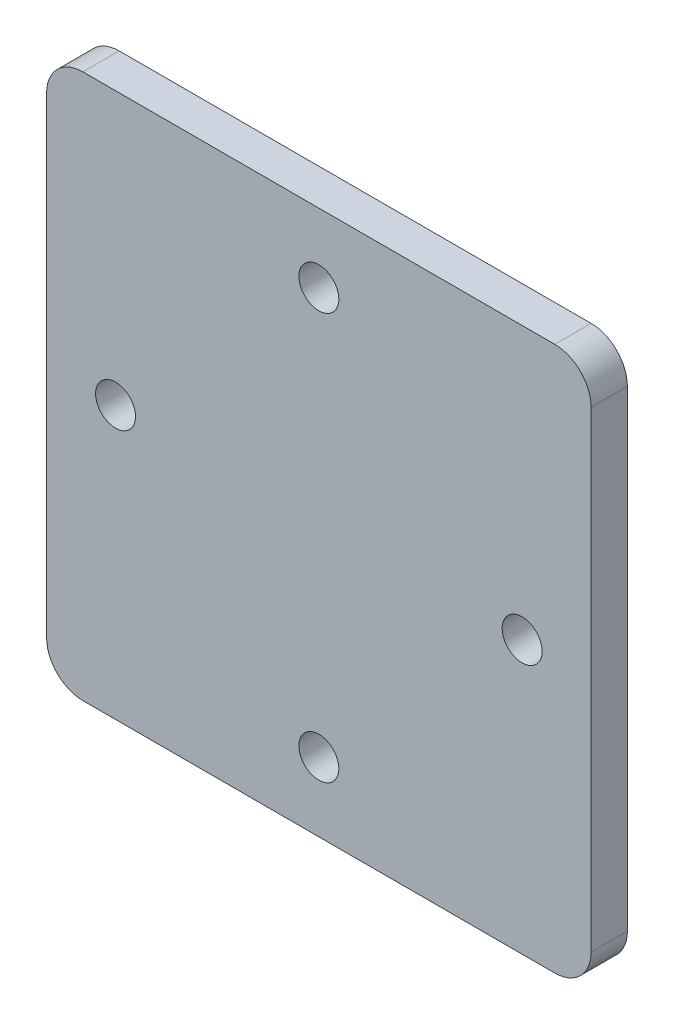
SolidWorks part; units mm, degrees
ref_plane "Frontale" through (0, 0, 0) normal (0, 0, 1) x (1, 0, 0)
ref_plane "Superiore" through (0, 0, 0) normal (0, 1, 0) x (1, 0, 0)
ref_plane "Destro" through (0, 0, 0) normal (1, 0, 0) x (0, 0, -1)
sketch "Schizzo1" plane through (0, 0, 0) normal (0, 0, 1) x (1, 0, 0)
  line L1 (65, -75) -> (-65, -75)
  line L2 (75, -65) -> (75, 65)
  line L3 (65, 75) -> (-65, 75)
  line L4 (-75, -65) -> (-75, 65)
  line L5 (75, -75) -> (-75, 75) construction
  line L6 (75, 75) -> (-75, -75) construction
  arc A0 (-65, 75) -> (-75, 65) centre (-65, 65) ccw
  arc A1 (75, 65) -> (65, 75) centre (65, 65) ccw
  arc A2 (75, -65) -> (65, -75) centre (65, -65) cw
  arc A3 (-65, -75) -> (-75, -65) centre (-65, -65) cw
  point P0 (0, 0)
  dimension "D1" = 10
  dimension "D2" = 150
  dimension "D3" = 150
extrude "Estrusione1" add sketch "Schizzo1" along normal blind 10
hole_wizard "M10 Giochi foro1" positions "Schizzo2" profile "Schizzo3" hole size "M10" standard "ISO" end condition through all
sketch "Schizzo2" plane through (-8.7763, -26.1291, 0) normal (0, 0, -1) x (-1, 0, 0)
  point P1 (-8.7762, 82.1292)
  point P3 (-8.7762, -29.8708)
  point P5 (-64.7762, 26.1292)
  point P7 (47.2238, 26.1292)
sketch "Schizzo3" plane through (0.0003, 56, 0) normal (1, 0, 0) x (0, 1, 0)
  line L0 (0, 0) -> (0, 10)
  line L1 (0, 10) -> (5.5, 10)
  line L2 (5.5, 10) -> (5.5, 0)
  line L5 (5.5, 0) -> (0, 0)
  line L11 (0, -6.35) -> (0, 107.95) construction
  dimension "Thru Hole Dia." = 11
  dimension "Thru Hole Depth" = 10
